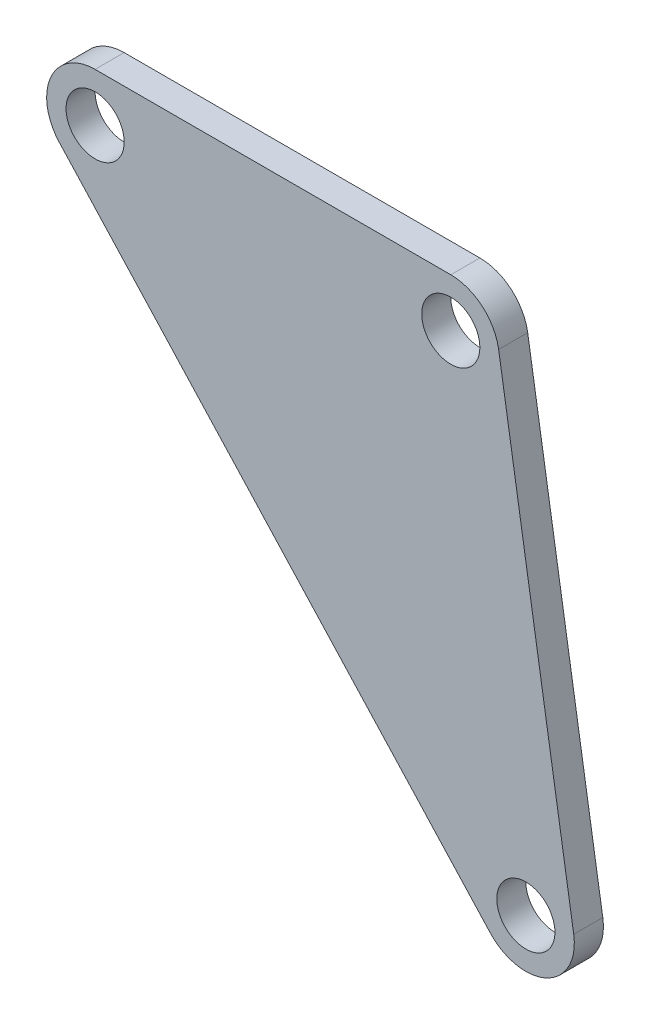
SolidWorks part; units mm, degrees
ref_plane "正面" through (0, 0, 0) normal (0, 0, 1) x (1, 0, 0)
ref_plane "平面" through (0, 0, 0) normal (0, 1, 0) x (1, 0, 0)
ref_plane "右側面" through (0, 0, 0) normal (1, 0, 0) x (0, 0, -1)
sketch "ｽｹｯﾁ1" plane through (0, 0, 0) normal (0, 0, 1) x (1, 0, 0)
  line L0 (-36.7, 0) -> (0, 0) construction
  line L1 (0, 0) -> (7.7466, -48.3838) construction
  line L2 (7.7466, -48.3838) -> (-36.7, 0) construction
  line L3 (-48.0826, 5) -> (15.3122, -64.0105)
  line L4 (15.3122, -64.0105) -> (4.2631, 5)
  line L5 (4.2631, 5) -> (-48.0826, 5)
  circle A0 centre (-36.7, 0) radius 3
  circle A1 centre (0, 0) radius 3
  circle A2 centre (7.7466, -48.3838) radius 3
  dimension "D4" = 6
  dimension "D1" = 36.7
  dimension "D2" = 49
  dimension "D3" = 65.7
  dimension "D5" = 5
  dimension "D6" = 5
  dimension "D7" = 5
extrude "ﾎﾞｽ - 押し出し1" add sketch "ｽｹｯﾁ1" along normal blind 3
fillet "ﾌｨﾚｯﾄ1" radius 5 3 edges at (15.3122, -64.0105, 1.5) (-48.0826, 5, 1.5) (4.2631, 5, 1.5)
